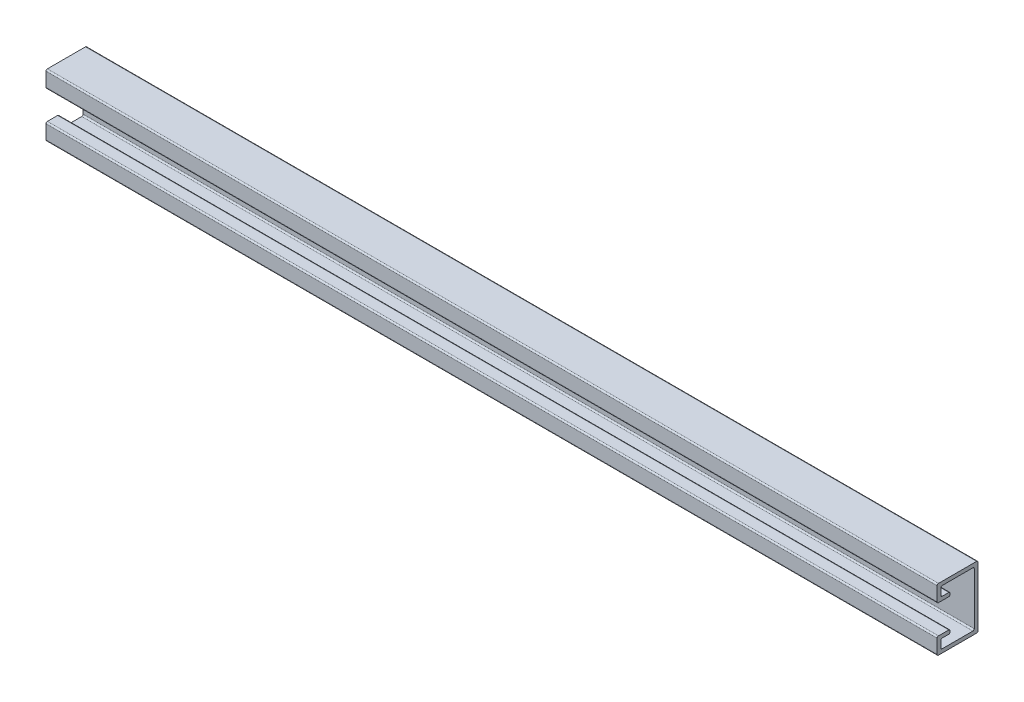
SolidWorks part; units mm, degrees
material "1060-O (SS)"
ref_plane "Front Plane" through (0, 0, 0) normal (0, 0, 1) x (1, 0, 0)
ref_plane "Top Plane" through (0, 0, 0) normal (0, 1, 0) x (1, 0, 0)
ref_plane "Right Plane" through (0, 0, 0) normal (1, 0, 0) x (0, 0, -1)
sketch "Sketch1" plane through (0, 0, 0) normal (1, 0, 0) x (0, 0, -1)
  line L0 (0, 0) -> (0, 74.93)
  line L7 (-45.72, 12.7) -> (-33.02, 12.7)
  line L8 (-45.72, 0) -> (-45.72, 12.7)
  line L9 (0, 0) -> (-45.72, 0)
  line L10 (-45.72, 62.23) -> (-33.02, 62.23)
  line L11 (-45.72, 74.93) -> (-45.72, 62.23)
  line L12 (0, 74.93) -> (-45.72, 74.93)
  dimension "D1" = 45.72
  dimension "D2" = 74.93
  dimension "D3" = 12.7
  dimension "D4" = 12.7
extrude "Extrude-Thin1" add sketch "Sketch1" along normal blind 1219.2 thin
fillet "Fillet1" radius 1.905 16 edges at (609.6, 12.7, 45.72) (609.6, 57.15, 50.8) (609.6, -5.08, 50.8) (609.6, 0, 0) (609.6, -5.08, -5.08) (609.6, 80.01, 50.8) (609.6, 80.01, -5.08) (609.6, 0, 45.72) (609.6, 17.78, 50.8) (609.6, 12.7, 33.02) (609.6, 17.78, 33.02) (609.6, 57.15, 33.02) (609.6, 62.23, 33.02) (609.6, 62.23, 45.72) (609.6, 74.93, 45.72) (609.6, 74.93, 0)
